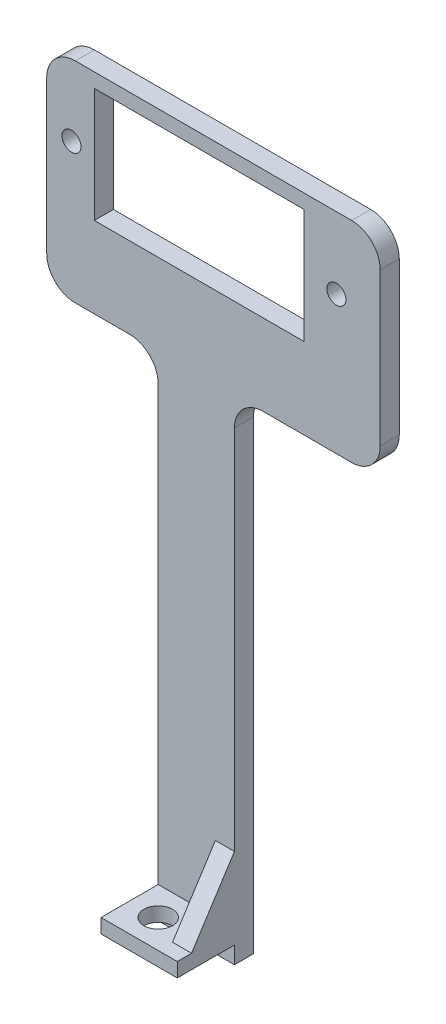
SolidWorks part; units mm, degrees
ref_plane "前视基准面" through (0, 0, 0) normal (0, 0, 1) x (1, 0, 0)
ref_plane "上视基准面" through (0, 0, 0) normal (0, 1, 0) x (1, 0, 0)
ref_plane "右视基准面" through (0, 0, 0) normal (1, 0, 0) x (0, 0, -1)
sketch "草图6" plane through (0, 0, 0) normal (0, 1, 0) x (1, 0, 0)
  line L1 (5, 3) -> (-3, 3)
  line L2 (5, 3) -> (5, -3)
  line L3 (5, -3) -> (-3, -3)
  line L4 (-3, 3) -> (-3, -3)
  line L6 (5, 0) -> (-3, 0) construction
  circle A0 centre (0, 0) radius 1.5
  dimension "D1" = 6
  dimension "D3" = 3
  dimension "D2" = 8
  dimension "D4" = 5
extrude "凸台-拉伸1" add sketch "草图6" along normal blind 1.5
sketch "草图7" plane through (0, 0, -3) normal (0, 0, -1) x (-1, 0, 0)
  line L1 (3, 0) -> (-5, 0)
  line L2 (3, 0) -> (3, 25)
  line L3 (3, 25) -> (-5, 25)
  line L4 (-5, 0) -> (-5, 25)
  line L5 (3, 0) -> (-5, 25) construction
  line L6 (3, 25) -> (-5, 0) construction
  point P4 (-1, 12.5)
  dimension "D1" = 8
  dimension "D2" = 25
extrude "凸台-拉伸2" add sketch "草图7" along normal blind 2
mirror "镜向1" about plane through (-3, 25, -5) normal (0, -1, 0) of bodies 109
sketch "草图8" plane through (0, 50, 0) normal (0, 1, 0) x (1, 0, 0)
  line L1 (-14.7, 3) -> (20.3, 3)
  line L2 (-14.7, 3) -> (-14.7, 5)
  line L3 (-14.7, 5) -> (20.3, 5)
  line L4 (20.3, 3) -> (20.3, 5)
  line L5 (-14.7, 3) -> (20.3, 5) construction
  line L6 (-14.7, 5) -> (20.3, 3) construction
  line L7 (5, 5) -> (-3, 5) construction
  line L8 (5, -3) -> (5, 5) construction
  point P4 (2.8, 4)
  dimension "D1" = 19.7
  dimension "D2" = 2
extrude "凸台-拉伸3" add sketch "草图8" along normal blind 22 contours L4 L3 L2 L1
sketch "草图9" plane through (0, 0, -5) normal (0, 0, -1) x (-1, 0, 0)
  line L2 (14.7, 72) -> (-20.3, 72) construction
  line L3 (9.7, 70.5) -> (-12.3, 70.5)
  line L4 (9.7, 70.5) -> (9.7, 58.5)
  line L5 (9.7, 58.5) -> (-12.3, 58.5)
  line L6 (-12.3, 70.5) -> (-12.3, 58.5)
  line L7 (9.7, 70.5) -> (-12.3, 58.5) construction
  line L8 (9.7, 58.5) -> (-12.3, 70.5) construction
  line L9 (14.7, 50) -> (14.7, 72) construction
  point P4 (14.7, 61)
  point P10 (-1.3, 64.5)
  dimension "D1" = 12
  dimension "D4" = 5
  dimension "D2" = 1.5
  dimension "D3" = 22
extrude "切除-拉伸1" cut sketch "草图9" against normal blind 10
ref_plane "基准面1" through (1, 0, 0) normal (-1, 0, 0) x (0, 0, 1)
sketch "草图12" plane through (1, 0, 0) normal (-1, 0, 0) x (0, 0, 1)
  line L0 (-4, 50) -> (-3, 41.5)
  line L1 (-3, 50) -> (-5, 50) construction
  line L2 (-3, 48.5) -> (-3, 1.5) construction
  line L3 (3, 48.5) -> (-3, 48.5) construction
  dimension "D1" = 7
sketch "草图14" plane through (0, 50, 0) normal (0, 1, 0) x (1, 0, 0)
  line L1 (5, 3) -> (-3, 3)
  line L2 (5, 3) -> (5, -3)
  line L3 (5, -3) -> (-3, -3)
  line L4 (-3, 3) -> (-3, -3)
  line L5 (5, 3) -> (-3, -3) construction
  line L6 (5, -3) -> (-3, 3) construction
  point P4 (1, 0)
extrude "切除-拉伸2" cut sketch "草图14" against normal blind 4.6
sketch "草图15" plane through (5, 0, 0) normal (1, 0, 0) x (0, 0, -1)
  line L0 (-1.5, 1.5) -> (3, 8.5)
  line L1 (-3, 1.5) -> (3, 1.5) construction
  line L2 (3, 50) -> (3, 1.5) construction
  dimension "D1" = 4.5
  dimension "D2" = 7
rib "筋3" sketch "草图15" sketch "草图15" thickness 2 extrusion direction parallel to sketch draft on no parameters "D1"=2
fillet "圆角2" radius 3 6 edges at (20.3, 50, -4) (5, 50, -4) (20.3, 72, -4) (-14.7, 72, -4) (-14.7, 50, -4) (-3, 50, -4)
sketch "草图16" plane through (0, 0, 0) normal (0, -1, 0) x (-1, 0, 0)
  line L0 (-5, -3) -> (-5, 5) construction
  line L1 (-5, 5) -> (3, 5)
  line L2 (-5, 5) -> (-5, 3)
  line L3 (-5, 3) -> (3, 3)
  line L4 (3, 5) -> (3, 3)
  line L5 (-5, 5) -> (3, 3) construction
  line L6 (-5, 3) -> (3, 5) construction
  line L7 (-5, 5) -> (3, 5) construction
  line L8 (3, 5) -> (3, -3) construction
  point P4 (-1, 4)
  dimension "D1" = 2
  dimension "D2" = 8
extrude "凸台-拉伸4" add sketch "草图16" along normal blind 1.8
sketch "草图17" plane through (0, 0, -5) normal (0, 0, -1) x (-1, 0, 0)
  line L0 (-20.3, 69) -> (-20.3, 53) construction
  line L1 (-8, 50) -> (-17.3, 50) construction
  line L2 (14.7, 69) -> (14.7, 53) construction
  line L3 (11.7, 50) -> (6, 50) construction
  circle A0 centre (-15.7, 64.5) radius 1
  circle A1 centre (12.1, 64.5) radius 1
  point P12 (8.85, 50)
  dimension "D1" = 4.6
  dimension "D2" = 14.5
  dimension "D3" = 2.6
  dimension "D4" = 14.5
extrude "切除-拉伸3" cut sketch "草图17" against normal blind 10
move or copy body "实体-移动/复制1" [suppressed] bodies to move or copy 118
